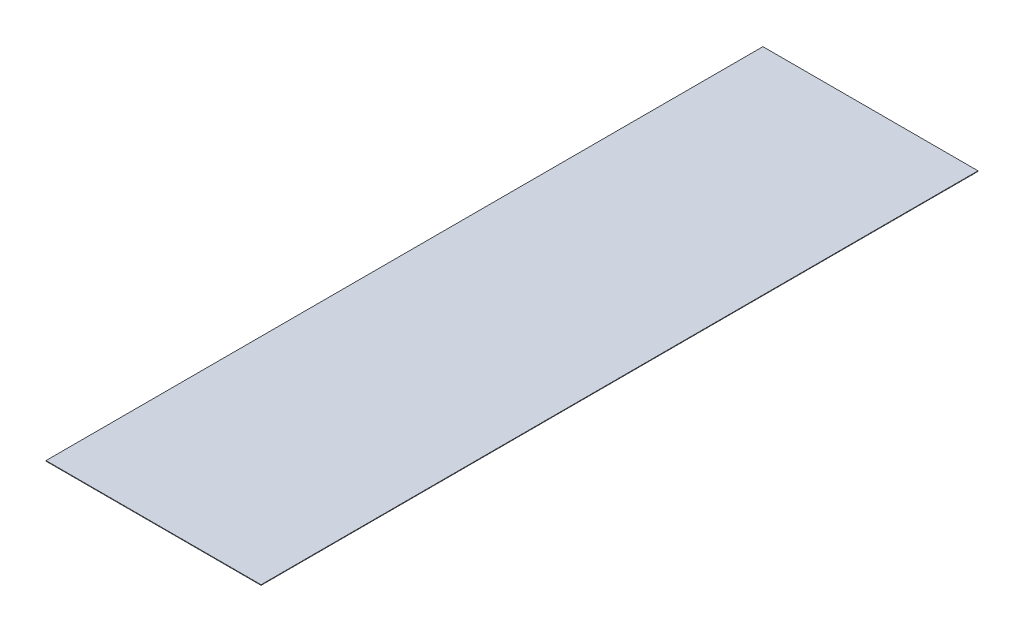
SolidWorks part; units mm, degrees
material "ASTM A36 Acero"
ref_plane "Alzado" through (0, 0, 0) normal (0, 0, 1) x (1, 0, 0)
ref_plane "Planta" through (0, 0, 0) normal (0, 1, 0) x (1, 0, 0)
ref_plane "Vista lateral" through (0, 0, 0) normal (1, 0, 0) x (0, 0, -1)
sketch "Croquis1" plane through (0, 0, 0) normal (0, 1, 0) x (1, 0, 0)
  line L1 (-457.2, -1524) -> (457.2, -1524)
  line L2 (-457.2, -1524) -> (-457.2, 1524)
  line L3 (-457.2, 1524) -> (457.2, 1524)
  line L4 (457.2, -1524) -> (457.2, 1524)
  line L5 (-457.2, -1524) -> (457.2, 1524) construction
  line L6 (-457.2, 1524) -> (457.2, -1524) construction
  point P0 (0, 0)
  dimension "D1" = 3048
  dimension "D2" = 914.4
extrude "Saliente-Extruir1" add sketch "Croquis1" along normal blind 2.3
